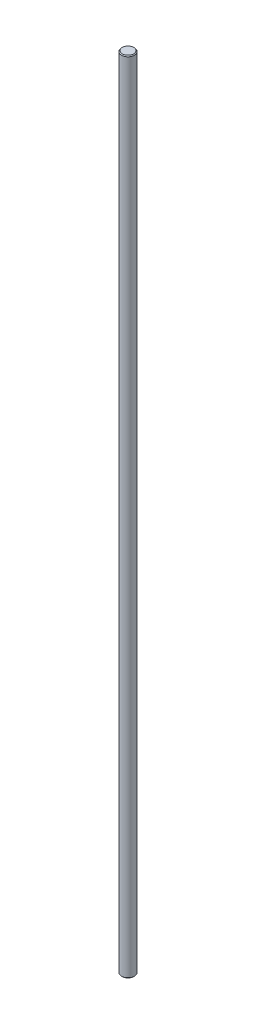
SolidWorks part; units mm, degrees
ref_plane "Front Plane" through (0, 0, 0) normal (0, 0, 1) x (1, 0, 0)
ref_plane "Top Plane" through (0, 0, 0) normal (0, 1, 0) x (1, 0, 0)
ref_plane "Right Plane" through (0, 0, 0) normal (1, 0, 0) x (0, 0, -1)
sketch "Sketch1" plane through (0, 0, 0) normal (0, 0, 1) x (1, 0, 0)
  line L0 (3.5, 495) -> (0, 495)
  line L1 (0, 495) -> (0, 0)
  line L2 (0, 0) -> (3.5, 0)
  line L3 (3.5, 0) -> (4, 0.5)
  line L4 (4, 0.5) -> (4, 494.5)
  line L5 (4, 494.5) -> (3.5, 495)
  line L6 (0, 495) -> (0, 0) construction
revolve "Revolve1" add sketch "Sketch1" angle 360 about L6
